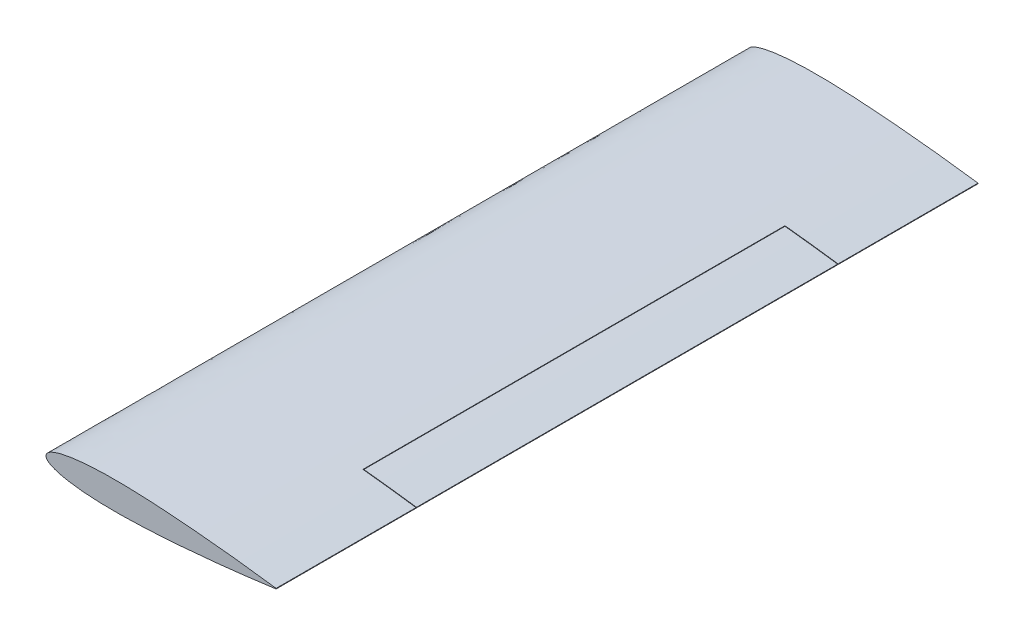
SolidWorks part; units mm, degrees
ref_plane "Front Plane" through (0, 0, 0) normal (0, 0, 1) x (1, 0, 0)
ref_plane "Top Plane" through (0, 0, 0) normal (0, 1, 0) x (1, 0, 0)
ref_plane "Right Plane" through (0, 0, 0) normal (1, 0, 0) x (0, 0, -1)
curve "Curve1"
  spline degree 3 poles (0, 0, 0) (0.003, 0.0365, 0) (0.009, 0.1114, 0) (0.0578, 0.22, 0) (0.134, 0.3245, 0) (0.2397, 0.4254, 0) (0.3736, 0.523, 0) (0.536, 0.6174, 0) (0.7264, 0.7086, 0) (0.9445, 0.7962, 0) (1.1898, 0.8801, 0) (1.462, 0.96, 0) (1.7603, 1.0355, 0) (2.0841, 1.1065, 0) (2.4327, 1.1725, 0) (2.8052, 1.2334, 0) (3.2008, 1.2888, 0) (3.6185, 1.3388, 0) (4.0575, 1.3829, 0) (4.5166, 1.4212, 0) (4.9948, 1.4535, 0) (5.491, 1.4798, 0) (6.0041, 1.5001, 0) (6.5327, 1.5144, 0) (7.0758, 1.5227, 0) (7.632, 1.5254, 0) (8.2001, 1.5224, 0) (8.7786, 1.514, 0) (9.3663, 1.5004, 0) (9.9618, 1.4819, 0) (10.5636, 1.4587, 0) (11.1705, 1.4311, 0) (11.7809, 1.3995, 0) (12.3935, 1.3642, 0) (13.0067, 1.3254, 0) (13.6193, 1.2836, 0) (14.2297, 1.2391, 0) (14.8366, 1.1921, 0) (15.4384, 1.1431, 0) (16.0339, 1.0922, 0) (16.6216, 1.0399, 0) (17.2001, 0.9864, 0) (17.7681, 0.9321, 0) (18.3242, 0.8771, 0) (18.8673, 0.8219, 0) (19.3959, 0.7666, 0) (19.9089, 0.7116, 0) (20.405, 0.657, 0) (20.8832, 0.6033, 0) (21.3422, 0.5505, 0) (21.7811, 0.499, 0) (22.1987, 0.449, 0) (22.5942, 0.4008, 0) (22.9666, 0.3545, 0) (23.3149, 0.3106, 0) (23.6385, 0.2691, 0) (23.9366, 0.2304, 0) (24.2084, 0.1946, 0) (24.4533, 0.1619, 0) (24.6708, 0.1326, 0) (24.8603, 0.1068, 0) (25.0214, 0.0847, 0) (25.1537, 0.0664, 0) (25.257, 0.052, 0) (25.3309, 0.0417, 0) (25.3753, 0.0355, 0) (25.3951, 0.0327, 0) (25.4, 0.032, 0) knots 0 0 0 0 0.004218 0.008652 0.013562 0.019137 0.0255 0.032726 0.040862 0.04993 0.05994 0.070892 0.082777 0.095581 0.109286 0.123868 0.139301 0.155557 0.172602 0.190404 0.208924 0.228125 0.247965 0.268401 0.289388 0.310881 0.332832 0.35519 0.377906 0.400928 0.424203 0.447679 0.471299 0.49501 0.518757 0.542484 0.566136 0.589657 0.612992 0.636087 0.658886 0.681338 0.703388 0.724985 0.746079 0.766619 0.786556 0.805845 0.82444 0.842296 0.859372 0.875627 0.891023 0.905523 0.919093 0.9317 0.943314 0.953909 0.963457 0.971937 0.979328 0.985613 0.990775 0.994804 0.997688 0.999422 1 1 1 1
curve "Curve2"
  spline degree 3 poles (0.0148, -0.1082, 0) (0.028, -0.1443, 0) (0.0559, -0.2205, 0) (0.1346, -0.3244, 0) (0.2395, -0.4254, 0) (0.3737, -0.523, 0) (0.536, -0.6174, 0) (0.7264, -0.7086, 0) (0.9445, -0.7962, 0) (1.1898, -0.8801, 0) (1.462, -0.96, 0) (1.7603, -1.0355, 0) (2.0841, -1.1065, 0) (2.4327, -1.1725, 0) (2.8052, -1.2334, 0) (3.2008, -1.2888, 0) (3.6185, -1.3388, 0) (4.0575, -1.3829, 0) (4.5166, -1.4212, 0) (4.9948, -1.4535, 0) (5.491, -1.4798, 0) (6.0041, -1.5001, 0) (6.5327, -1.5144, 0) (7.0758, -1.5227, 0) (7.632, -1.5254, 0) (8.2001, -1.5224, 0) (8.7786, -1.514, 0) (9.3663, -1.5004, 0) (9.9618, -1.4819, 0) (10.5636, -1.4587, 0) (11.1705, -1.4311, 0) (11.7809, -1.3995, 0) (12.3935, -1.3642, 0) (13.0067, -1.3254, 0) (13.6193, -1.2836, 0) (14.2297, -1.2391, 0) (14.8366, -1.1921, 0) (15.4384, -1.1431, 0) (16.0339, -1.0922, 0) (16.6216, -1.0399, 0) (17.2001, -0.9864, 0) (17.7681, -0.9321, 0) (18.3242, -0.8771, 0) (18.8673, -0.8219, 0) (19.3959, -0.7666, 0) (19.9089, -0.7116, 0) (20.405, -0.657, 0) (20.8832, -0.6033, 0) (21.3422, -0.5505, 0) (21.7811, -0.499, 0) (22.1987, -0.449, 0) (22.5942, -0.4008, 0) (22.9666, -0.3545, 0) (23.3149, -0.3106, 0) (23.6385, -0.2691, 0) (23.9366, -0.2304, 0) (24.2084, -0.1946, 0) (24.4533, -0.1619, 0) (24.6708, -0.1326, 0) (24.8603, -0.1068, 0) (25.0214, -0.0847, 0) (25.1537, -0.0664, 0) (25.257, -0.052, 0) (25.3309, -0.0417, 0) (25.3753, -0.0355, 0) (25.3951, -0.0327, 0) (25.4, -0.032, 0) knots 0 0 0 0 0.004453 0.009384 0.014983 0.021372 0.028629 0.036799 0.045906 0.055959 0.066957 0.078892 0.091751 0.105513 0.120157 0.135656 0.15198 0.169098 0.186975 0.205574 0.224856 0.24478 0.265302 0.286379 0.307962 0.330006 0.352459 0.375271 0.398391 0.421765 0.445339 0.46906 0.492871 0.516719 0.540546 0.564298 0.587919 0.611353 0.634545 0.657442 0.679988 0.702132 0.723821 0.745003 0.76563 0.785652 0.805023 0.823696 0.841628 0.858776 0.8751 0.890561 0.905123 0.91875 0.93141 0.943074 0.953713 0.963302 0.971818 0.979241 0.985552 0.990736 0.994782 0.997678 0.999419 1 1 1 1
sketch "Sketch1" plane through (0, 0, 0) normal (0, 0, 1) x (1, 0, 0)
  line L0 (0, 0) -> (0.0742, -0.5411)
  line L1 (127, 0.16) -> (127, -0.16)
  spline S2 degree 3 poles (0.0742, -0.5411) (0.1402, -0.7217) (0.2794, -1.1023) (0.673, -1.6219) (1.1974, -2.1272) (1.8685, -2.615) (2.6798, -3.0872) (3.6318, -3.5429) (4.7223, -3.9812) (5.9492, -4.4007) (7.31, -4.8) (8.8016, -5.1777) (10.4206, -5.5323) (12.1634, -5.8624) (14.0259, -6.1668) (16.0039, -6.4442) (18.0926, -6.6938) (20.2874, -6.9146) (22.583, -7.106) (24.9741, -7.2675) (27.4552, -7.3989) (30.0204, -7.5003) (32.6637, -7.5718) (35.3791, -7.6137) (38.1601, -7.6269) (41.0003, -7.6119) (43.8929, -7.5699) (46.8314, -7.5019) (49.8088, -7.4093) (52.8181, -7.2933) (55.8524, -7.1556) (58.9045, -6.9976) (62.9897, -6.7619) (67.0743, -6.4928) (72.1532, -6.1221) (77.1616, -5.7236) (82.1152, -5.2913) (86.9285, -4.8463) (91.5567, -4.3963) (96.0742, -3.9303) (100.3424, -3.4723) (104.3213, -3.0299) (108.8003, -2.5098) (112.8562, -2.0199) (115.9539, -1.6325) (118.1927, -1.3456) (120.4545, -1.0515) (122.9821, -0.715) (125.1839, -0.4131) (126.3836, -0.2463) (126.7779, -0.1912) (127, -0.16) knots 0 0 0 0 0.004453 0.009384 0.014983 0.021372 0.028629 0.036799 0.045906 0.055959 0.066957 0.078892 0.091751 0.105513 0.120157 0.135656 0.15198 0.169098 0.186975 0.205574 0.224856 0.24478 0.265302 0.286379 0.307962 0.330006 0.352459 0.375271 0.398391 0.421765 0.445339 0.46906 0.492871 0.540546 0.564298 0.611353 0.657442 0.679988 0.723821 0.76563 0.785652 0.823696 0.858776 0.890561 0.91875 0.93141 0.943074 0.971818 0.990736 0.994782 1 1 1 1
  spline S3 degree 3 poles (0, 0) (0.0148, 0.1826) (0.0451, 0.5571) (0.2892, 1.1001) (0.6698, 1.6226) (1.1984, 2.127) (1.8682, 2.615) (2.6799, 3.0872) (3.6318, 3.5429) (4.7223, 3.9812) (5.9492, 4.4007) (7.31, 4.8) (8.8016, 5.1777) (10.4206, 5.5323) (12.1634, 5.8624) (14.0259, 6.1668) (16.0039, 6.4442) (18.0926, 6.6938) (20.2874, 6.9146) (22.583, 7.106) (24.9741, 7.2675) (27.4552, 7.3989) (30.0204, 7.5003) (32.6637, 7.5718) (35.3791, 7.6137) (38.1601, 7.6269) (41.0003, 7.6119) (43.8929, 7.5699) (46.8314, 7.5019) (49.8088, 7.4093) (52.8181, 7.2933) (55.8524, 7.1556) (58.9045, 6.9976) (62.9897, 6.7619) (67.0743, 6.4928) (72.1532, 6.1221) (77.1616, 5.7236) (82.1152, 5.2913) (86.9285, 4.8463) (91.5567, 4.3963) (96.0742, 3.9303) (100.3424, 3.4723) (104.3213, 3.0299) (108.8003, 2.5098) (112.8562, 2.0199) (115.9539, 1.6325) (118.1927, 1.3456) (120.4545, 1.0515) (122.9821, 0.715) (125.1839, 0.4131) (126.3836, 0.2463) (126.7779, 0.1912) (127, 0.16) knots 0 0 0 0 0.004218 0.008652 0.013562 0.019137 0.0255 0.032726 0.040862 0.04993 0.05994 0.070892 0.082777 0.095581 0.109286 0.123868 0.139301 0.155557 0.172602 0.190404 0.208924 0.228125 0.247965 0.268401 0.289388 0.310881 0.332832 0.35519 0.377906 0.400928 0.424203 0.447679 0.471299 0.49501 0.542484 0.566136 0.612992 0.658886 0.681338 0.724985 0.766619 0.786556 0.82444 0.859372 0.891023 0.919093 0.9317 0.943314 0.971937 0.990775 0.994804 1 1 1 1
  point P0 (127, 0)
  dimension "D1" = 127
extrude "Boss-Extrude1" add sketch "Sketch1" along normal blind 387.35
sketch "Sketch2" plane through (0, 0, 0) normal (0, 1, 0) x (1, 0, 0)
  line L0 (0, 0) -> (0, -193.675) construction
  line L1 (0, -387.35) -> (0, 0) construction
  line L2 (0, -193.675) -> (127, -193.675) construction
  line L3 (127, -387.35) -> (127, 0) construction
  line L5 (114.3, -206.375) -> (12.7, -206.375)
  line L6 (114.3, -206.375) -> (114.3, -180.975)
  line L7 (114.3, -180.975) -> (12.7, -180.975)
  line L8 (12.7, -206.375) -> (12.7, -180.975)
  line L9 (114.3, -206.375) -> (12.7, -180.975) construction
  line L10 (114.3, -180.975) -> (12.7, -206.375) construction
  point P5 (63.5, -193.675)
  point P14 (63.5, -193.675)
  point P17 (63.5, -193.675)
  dimension "D1" = 101.6
  dimension "D2" = 25.4
hole_wizard "1/4 (0.25) Diameter Hole1" positions "Sketch2" profile "Sketch4" hole size "1/4" standard "ANSI Inch"
sketch "Sketch4" plane through (76.2, 0, 254) normal (1, 0, 0) x (0, 0, -1)
  line L0 (0, 0) -> (0, 9.1522)
  line L1 (0, 9.1522) -> (3.175, 9.1522)
  line L2 (3.175, 9.1522) -> (3.175, 0)
  line L5 (3.175, 0) -> (0, 0)
  line L11 (0, -6.35) -> (0, 107.95) construction
  dimension "Thru Hole Dia." = 6.35
  dimension "Thru Hole Depth" = 9.1522
ref_plane "Plane1" through (0, 25.4, 0) normal (0, 1, 0) x (1, 0, 0)
sketch "Sketch5" plane through (0, 25.4, 0) normal (0, 1, 0) x (1, 0, 0)
  line L4 (12.7, -206.375) -> (114.3, -206.375)
  line L5 (12.7, -180.975) -> (12.7, -206.375)
  line L6 (114.3, -180.975) -> (12.7, -180.975)
  line L7 (114.3, -206.375) -> (114.3, -180.975)
  line L8 (12.7, -206.375) -> (114.3, -206.375)
  line L9 (12.7, -180.975) -> (12.7, -206.375)
  line L10 (114.3, -180.975) -> (12.7, -180.975)
  line L11 (114.3, -206.375) -> (114.3, -180.975)
  dimension "D1" = 0
hole_wizard "1/4 (0.25) Diameter Hole3" positions "Sketch5" profile "Sketch7" hole size "1/4" standard "ANSI Inch"
sketch "Sketch7" plane through (127, 25.4, 266.7) normal (1, 0, 0) x (0, 0, 1)
  line L0 (0, 0) -> (0, 34.5522)
  line L1 (0, 34.5522) -> (3.175, 34.5522)
  line L2 (3.175, 34.5522) -> (3.175, 0)
  line L5 (3.175, 0) -> (0, 0)
  line L11 (0, -6.35) -> (0, 107.95) construction
  dimension "Thru Hole Dia." = 6.35
  dimension "Thru Hole Depth" = 34.5522
sketch "Sketch8" plane through (0, 0, 0) normal (0, 1, 0) x (1, 0, 0)
  line L0 (127, 0) -> (127, -77.47) construction
  line L1 (156.0513, -309.88) -> (97.9488, -309.88)
  line L2 (156.0513, -309.88) -> (156.0513, -77.47)
  line L3 (156.0513, -77.47) -> (97.9488, -77.47)
  line L4 (97.9488, -309.88) -> (97.9488, -77.47)
  dimension "D1" = 77.47
  dimension "D2" = 232.41
  dimension "D3" = 58.1025
extrude "Cut-Extrude-Thin1" cut sketch "Sketch8" against normal blind 25.4 and the other way blind 25.4 thin thin type one direction wall 0.254
equation "\"span\"= 48"
equation "\"wing_chord\"= 9"
equation "\"fuse_len\"= 15"
equation "\"fuse_height\"= 5"
equation "\"fuse_wid\"= 5"
equation "\"foam_t\"= 0.1875"
equation "\"main_spar_len\"= 36"
equation "\"x_fuse_to_wing\"= 3"
equation "\"x_cg_from_le\"= 2.25"
equation "\"boom_len\"= 30"
equation "\"wing_angle\"= 1.5"
equation "\"boom_d\"= 0.75"
equation "\"wing_spar_d\"= 0.375"
equation "\"wing_spar_l\"= 48"
equation "\"wing_spar_spacing\"= 1.35"
equation "\"wing_mount_l\"= 2.5"
equation "\"vstab_span\"= 6.5"
equation "\"hstab_span\"= 15.25"
equation "\"tail_chord\"= 5"
equation "\"D1@Boss-Extrude1\"=\"hstab_span\""
equation "\"D1@Sketch8\"=\"hstab_span\"*0.2"
equation "\"D2@Sketch8\"=\"hstab_span\"*0.6"
equation "\"D3@Sketch8\"=\"hstab_span\"*0.15"
